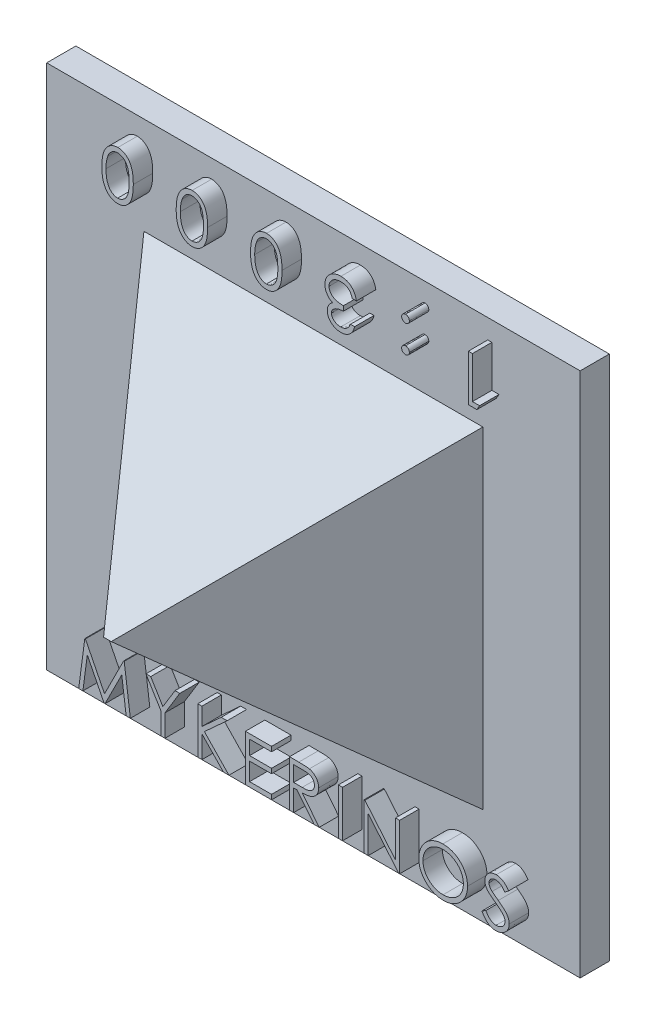
SolidWorks part; units mm, degrees
ref_plane "Plan de face" through (0, 0, 0) normal (0, 0, 1) x (1, 0, 0)
ref_plane "Plan de dessus" through (0, 0, 0) normal (0, 1, 0) x (1, 0, 0)
ref_plane "Plan de droite" through (0, 0, 0) normal (1, 0, 0) x (0, 0, -1)
sketch "Esquisse1" plane through (0, 0, 0) normal (0, 0, 1) x (1, 0, 0)
  line L1 (0, 0) -> (34.85, 0)
  line L2 (0, 0) -> (0, 34.065)
  line L3 (0, 34.065) -> (34.85, 34.065)
  line L4 (34.85, 0) -> (34.85, 34.065)
  dimension "D1" = 34.85
  dimension "D2" = 34.065
extrude "Boss.-Extru.1" add sketch "Esquisse1" along normal blind 50 draft 38.8
sketch "Esquisse3" plane through (0, 0, 0) normal (0, 0, -1) x (-1, 0, 0)
  line L8 (10, -10) -> (10, 44.065)
  line L9 (10, 44.065) -> (-44.85, 44.065)
  line L10 (-44.85, 44.065) -> (-44.85, -10)
  line L11 (-44.85, -10) -> (10, -10)
  line L12 (10, -10) -> (10, 44.065)
  line L13 (10, 44.065) -> (-44.85, 44.065)
  line L14 (-44.85, 44.065) -> (-44.85, -10)
  line L15 (-44.85, -10) -> (10, -10)
  dimension "D1" = 10
extrude "Boss.-Extru.3" add sketch "Esquisse3" along normal blind 3 separate body
sketch "Esquisse2" plane through (0, 0, -3) normal (0, 0, -1) x (-1, 0, 0)
  line L0 (0, 0) -> (-34.85, 0) construction
  line L1 (0, 34.065) -> (0, 0) construction
  circle A0 centre (-17.425, 17.0325) radius 23.25
  point P5 (-17.425, 0)
  point P8 (0, 17.0325)
  dimension "D1" = 46.5
extrude "Boss.-Extru.2" [suppressed] add sketch "Esquisse2" along normal blind 30
sketch "Esquisse4" plane through (0, 0, 0) normal (0, 0, 1) x (1, 0, 0)
  line L0 (-5.075, -8) -> (39.925, -8) construction
  line L1 (-2.575, 42.065) -> (37.425, 42.065) construction
  line L2 (0, 0) -> (34.85, 0) construction
  line L3 (44.85, -10) -> (-10, -10) construction
  line L4 (34.85, 34.065) -> (0, 34.065) construction
  line L5 (-10, 44.065) -> (44.85, 44.065) construction
  text T0 "MYKERINOS" font "Century Gothic" height in points 18
  text T1 "1:3000" font "Century Gothic" height in points 18
  point P6 (17.425, 0)
  point P7 (17.425, -8)
  point P12 (17.425, 34.065)
  point P13 (17.425, 42.065)
  dimension "D1" = 2
  dimension "D2" = 2
  dimension "D3" = 45
  dimension "D4" = 40
extrude "Boss.-Extru.4" add sketch "Esquisse4" along normal blind 2
